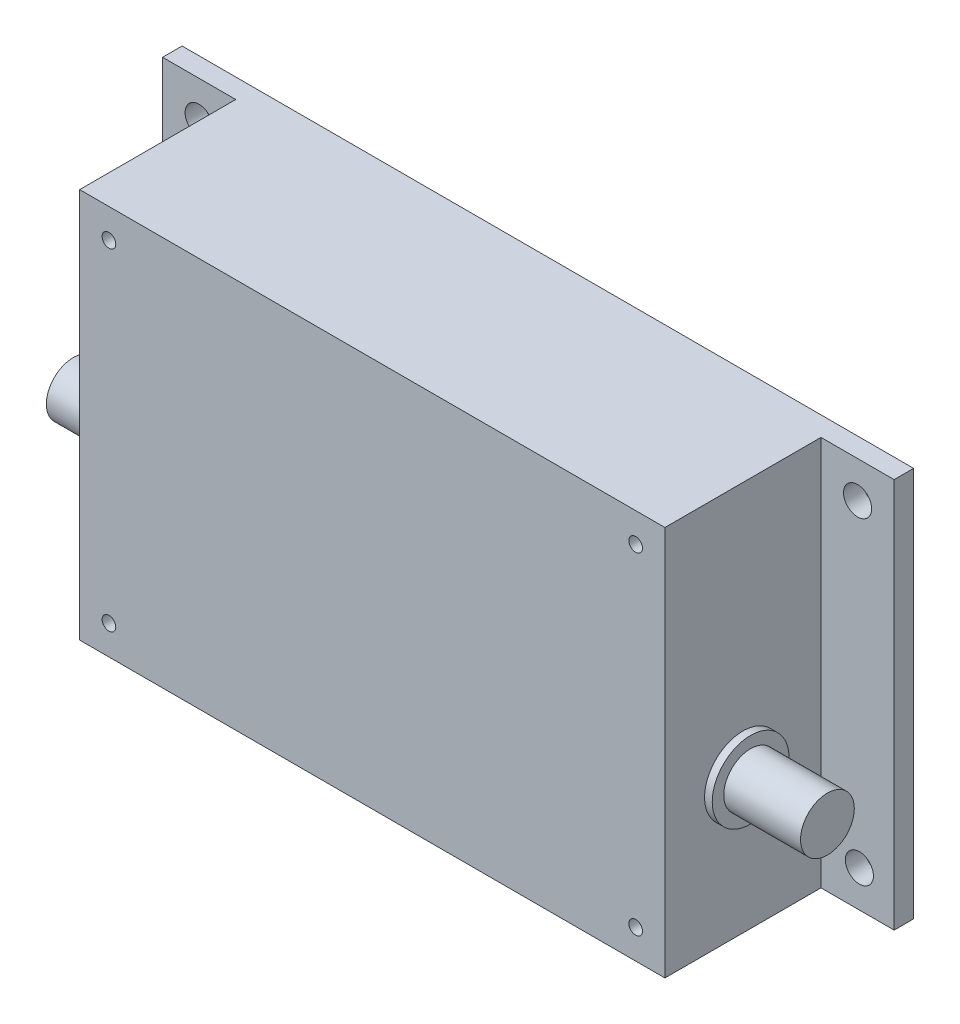
SolidWorks part; units mm, degrees
ref_plane "Płaszczyzna przednia" through (0, 0, 0) normal (0, 0, 1) x (1, 0, 0)
ref_plane "Płaszczyzna górna" through (0, 0, 0) normal (0, 1, 0) x (1, 0, 0)
ref_plane "Płaszczyzna prawa" through (0, 0, 0) normal (1, 0, 0) x (0, 0, -1)
sketch "Szkic1" plane through (0, 0, 0) normal (0, 0, 1) x (1, 0, 0)
  line L1 (-51.0551, 25.6684) -> (44.1949, 25.6684)
  line L2 (-51.0551, 25.6684) -> (-51.0551, -25.1316)
  line L3 (-51.0551, -25.1316) -> (44.1949, -25.1316)
  line L4 (44.1949, 25.6684) -> (44.1949, -25.1316)
  circle A0 centre (-46.0607, -20.3716) radius 1.83
  circle A1 centre (-46.2951, 20.9084) radius 1.83
  circle A2 centre (39.4349, 20.9084) radius 1.83
  circle A3 centre (39.6693, -20.3716) radius 1.83
  point P12 (0, 0)
  point P13 (0, 0)
  point P14 (-47.4257, 20.9101)
  point P15 (0, 0)
  point P16 (4.5582, -26.6376)
  dimension "D3" = 41.28
  dimension "D1" = 95.25
  dimension "D2" = 50.8
  dimension "D4" = 85.73
  dimension "D5" = 4.76
  dimension "D6" = 4.76
  dimension "D7" = 4.76
  dimension "D8" = 4.76
  dimension "D9" = 4.76
extrude "Dodanie-wyciągnięcie1" add sketch "Szkic1" along normal blind 2.54
sketch "Szkic2" plane through (0, 0, 2.54) normal (0, 0, 1) x (1, 0, 0)
  line L0 (44.1949, 25.6684) -> (-51.0551, 25.6684) construction
  line L1 (-41.5301, 25.6684) -> (34.6699, 25.6684)
  line L2 (-41.5301, 25.6684) -> (-41.5301, -25.1316)
  line L3 (-41.5301, -25.1316) -> (34.6699, -25.1316)
  line L4 (34.6699, 25.6684) -> (34.6699, -25.1316)
  line L5 (-51.0551, -25.1316) -> (44.1949, -25.1316) construction
  line L6 (-51.0551, 25.6684) -> (-51.0551, -25.1316) construction
  dimension "D1" = 76.2
  dimension "D2" = 9.525
extrude "Dodanie-wyciągnięcie2" add sketch "Szkic2" along normal blind 20.32
hole_wizard "Otwór #50 (0.07)1" positions "Szkic3" profile "Szkic5" hole size "#50" standard "Ansi Inch"
sketch "Szkic3" plane through (0, 0, 22.86) normal (0, 0, 1) x (1, 0, 0)
  line L1 (-41.5301, 25.6684) -> (-41.5301, -25.1316) construction
  line L2 (-41.5301, -25.1316) -> (34.6699, -25.1316) construction
  point P0 (-37.7201, 21.8584)
  point P2 (30.8599, 21.8584)
  point P4 (30.8599, -21.3216)
  point P6 (-37.7201, -21.3216)
  point P23 (0, 0)
  point P24 (27.0203, 21.8584)
  point P25 (29.1848, 21.8584)
  dimension "D1" = 43.18
  dimension "D2" = 68.58
  dimension "D3" = 3.81
  dimension "D4" = 3.81
  dimension "D5" = 3.81
  dimension "D6" = 0
  dimension "D7" = 68.58
sketch "Szkic5" plane through (-37.7201, 21.8584, 22.86) normal (1, 0, 0) x (0, -1, 0)
  line L0 (0, 0) -> (0, 5.5342)
  line L1 (0, 5.5342) -> (0.889, 5)
  line L2 (0.889, 5) -> (0.889, 0)
  line L5 (0.889, 0) -> (0, 0)
  line L10 (0, 5.5342) -> (-0.889, 5) construction
  line L11 (0, -6.35) -> (0, 107.95) construction
  dimension "Średnica otworu" = 1.778
  dimension "Głębokość otworu" = 5
  dimension "Kąt wiertła" = 118
sketch "Szkic6" plane through (-41.5301, 0, 0) normal (-1, 0, 0) x (0, 0, 1)
  line L0 (0, 25.6684) -> (0, -25.1316) construction
  line L1 (22.86, 25.6684) -> (2.54, 25.6684) construction
  circle A0 centre (12.7, -7.3516) radius 3.5
  dimension "D1" = 12.7
  dimension "D2" = 33.02
extrude "Dodanie-wyciągnięcie3" add sketch "Szkic6" along normal blind 11
sketch "Szkic7" plane through (-41.5301, 0, 0) normal (-1, 0, 0) x (0, 0, 1)
  circle A4 centre (12.7, -7.3516) radius 5
  circle A5 centre (12.7, -7.3516) radius 5
  point P2 (12.6909, -7.9282)
  dimension "D1" = 1.5
extrude "Dodanie-wyciągnięcie4" add sketch "Szkic7" along normal blind 1
sketch "Szkic8" plane through (34.6699, 0, 0) normal (1, 0, 0) x (0, 0, -1)
  line L0 (-22.86, 25.6684) -> (-2.54, 25.6684) construction
  line L1 (0, -25.1316) -> (0, 25.6684) construction
  circle A0 centre (-12.7, -7.3516) radius 3.5
  dimension "D1" = 33.02
  dimension "D2" = 12.7
extrude "Dodanie-wyciągnięcie5" add sketch "Szkic8" along normal blind 11
sketch "Szkic9" plane through (34.6699, 0, 0) normal (1, 0, 0) x (0, 0, -1)
  circle A2 centre (-12.7, -7.3516) radius 5
  circle A3 centre (-12.7, -7.3516) radius 5
  dimension "D1" = 1.5
extrude "Dodanie-wyciągnięcie6" add sketch "Szkic9" along normal blind 1
sketch "Szkic10" plane through (-41.5301, 0, 0) normal (-1, 0, 0) x (0, 0, 1)
  line L0 (22.86, 25.6684) -> (2.54, 25.6684) construction
  line L1 (0, 25.6684) -> (0, -25.1316) construction
  circle A0 centre (10.16, 12.9684) radius 0.5
  dimension "D1" = 12.7
  dimension "D2" = 10.16
extrude "Dodanie-wyciągnięcie7" add sketch "Szkic10" along normal blind 10
sketch "Szkic11" plane through (-41.5301, 0, 0) normal (-1, 0, 0) x (0, 0, 1)
  circle A2 centre (10.16, 12.9684) radius 4
  circle A3 centre (10.16, 12.9684) radius 4
  dimension "D1" = 3.5
sketch "Szkic12" plane through (-51.5301, 0, 0) normal (-1, 0, 0) x (0, 0, 1)
  circle A0 centre (10.16, 12.9684) radius 1.0593
extrude "Dodanie-wyciągnięcie8" add sketch "Szkic12" against normal blind 1
extrude "Dodanie-wyciągnięcie9" add sketch "Szkic11" along normal blind 1
